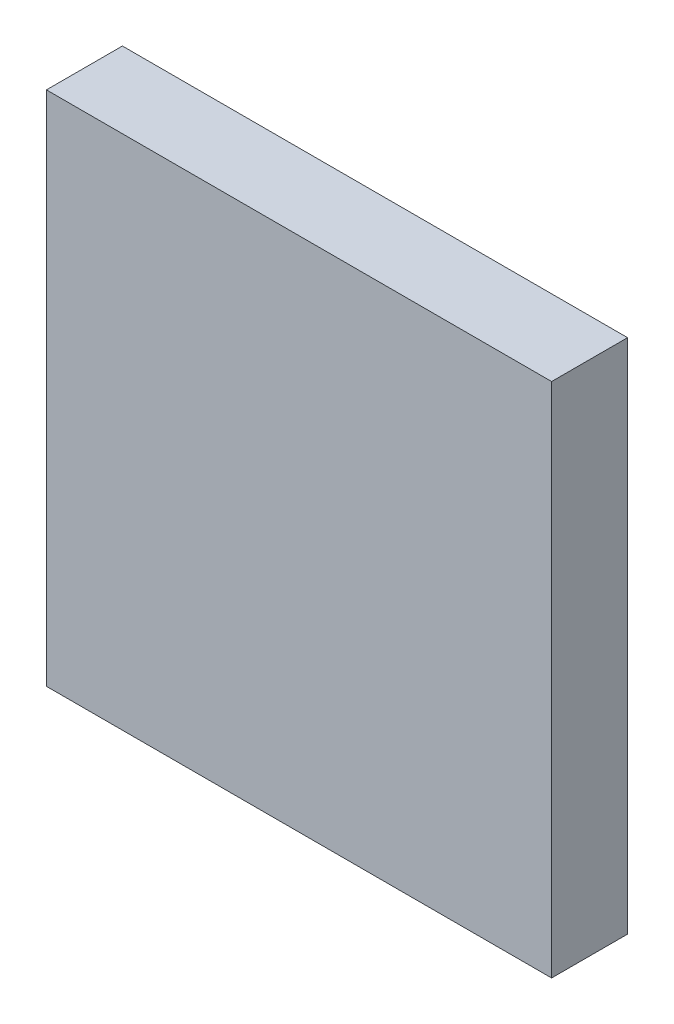
SolidWorks part; units mm, degrees
ref_plane "Plano frontal" through (0, 0, 0) normal (0, 0, 1) x (1, 0, 0)
ref_plane "Plano superior" through (0, 0, 0) normal (0, 1, 0) x (1, 0, 0)
ref_plane "Plano direito" through (0, 0, 0) normal (1, 0, 0) x (0, 0, -1)
sketch "Esboço1" plane through (0, 0, 0) normal (0, 0, 1) x (1, 0, 0)
  line L1 (-33.25, -34) -> (33.25, -34)
  line L2 (-33.25, -34) -> (-33.25, 34)
  line L3 (-33.25, 34) -> (33.25, 34)
  line L4 (33.25, -34) -> (33.25, 34)
  line L5 (-33.25, -34) -> (33.25, 34) construction
  line L6 (-33.25, 34) -> (33.25, -34) construction
  point P0 (0, 0)
  dimension "D1" = 68
  dimension "D2" = 66.5
extrude "Ressalto-extrusão1" add sketch "Esboço1" along normal blind 10
